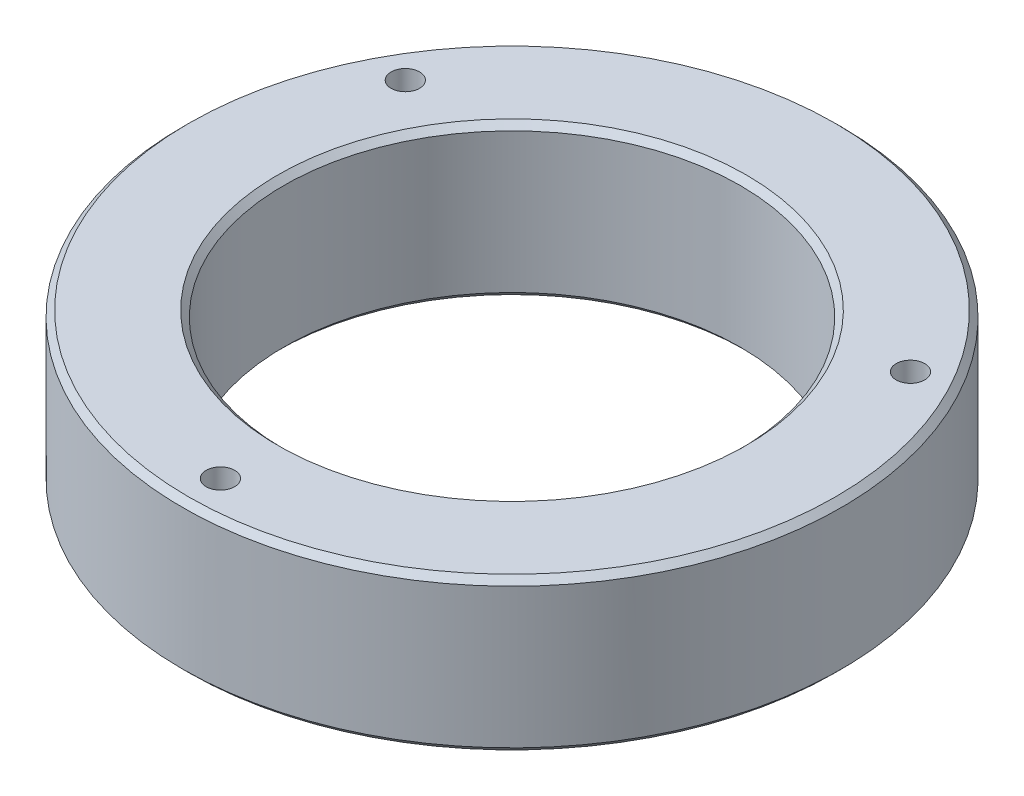
SolidWorks part; units mm, degrees
ref_plane "Front Plane" through (0, 0, 0) normal (1, 0, 0) x (0, 1, 0)
ref_plane "Top Plane" through (0, 0, 0) normal (0, 0, 1) x (0, 1, 0)
ref_plane "Right Plane" through (0, 0, 0) normal (0, 1, 0) x (-1, 0, 0)
sketch "Sketch1" plane through (0, 0, 0) normal (0, 0, 1) x (0, 1, 0)
  line L0 (-19.05, 82.5246) -> (19.05, 82.5246)
  line L1 (19.05, 82.5246) -> (19.05, 57.15)
  line L2 (19.05, 57.15) -> (-19.05, 57.15)
  line L3 (-19.05, 57.15) -> (-19.05, 82.5246)
  line L4 (-44.45, 0) -> (44.45, 0) construction
  point P6 (0, 0)
  dimension "D1" = 38.1
  dimension "D2" = 25.3746
  dimension "D3" = 82.5246
  dimension "D4" = 19.05
revolve "Revolve1" add sketch "Sketch1" angle 360 about L4
hole_wizard "CBORE for 1/4 Socket Head Cap Screw1" positions "Sketch3" profile "Sketch2" counterbore size "1/4" standard "ANSI Inch"
sketch "Sketch3" plane through (0, -19.05, 0) normal (0, -1, 0) x (-1, 0, 0)
  circle A0 centre (0, 0.0068) radius 73.0318 construction
  circle A1 centre (0, 0) radius 57.15 construction
  point P0 (0, -73.025)
  point P1 (-63.246, 36.5252)
  point P3 (63.246, 36.5252)
  dimension "D1" = 146.0637
  dimension "D2" = 63.246
  dimension "D3" = 63.246
  dimension "D4" = 0.0068
  dimension "D5" = 36.5252
  dimension "D6" = 73.025
sketch "Sketch2" plane through (0, -19.05, 73.025) normal (1, 0, 0) x (0, 0, -1)
  line L0 (0, 0) -> (0, 40.2443)
  line L1 (0, 40.2443) -> (3.5687, 38.1)
  line L2 (3.5687, 38.1) -> (3.5687, 9.652)
  line L3 (3.5687, 9.652) -> (5.5626, 9.652)
  line L4 (5.5626, 9.652) -> (5.5626, 0)
  line L5 (5.5626, 0) -> (0, 0)
  line L10 (0, 40.2443) -> (-3.5687, 38.1) construction
  line L11 (0, -6.35) -> (0, 107.95) construction
  dimension "Hole Dia." = 7.1374
  dimension "Hole Depth" = 38.1
  dimension "C'Bore Dia." = 11.1252
  dimension "C'Bore Depth" = 9.652
  dimension "Drill Angle" = 118
hole_wizard "3/8-16 Tapped Hole2" positions "Sketch7" profile "Sketch6" tap size "3/8-16" standard "ANSI Inch"
sketch "Sketch7" plane through (0, -19.05, 0) normal (0, -1, 0) x (-1, 0, 0)
  circle A0 centre (0, -73.025) radius 5.5626 construction
  point P0 (-69.85, 0)
  point P1 (69.85, 0)
  dimension "D1" = 69.85
  dimension "D2" = 69.85
  dimension "D3" = 73.025
  dimension "D4" = 73.025
sketch "Sketch6" plane through (69.85, -19.05, 0) normal (1, 0, 0) x (0, 0, -1)
  line L0 (0, 0) -> (0, 27.7847)
  line L1 (0, 27.7847) -> (3.9687, 25.4)
  line L2 (3.9687, 25.4) -> (3.9687, 0)
  line L5 (3.9687, 0) -> (0, 0)
  line L10 (0, 27.7847) -> (-3.9687, 25.4) construction
  line L11 (0, -6.35) -> (0, 107.95) construction
  dimension "Tap Drill Dia." = 7.9375
  dimension "Tap Drill Depth" = 25.4
  dimension "Drill Angle" = 118
cosmetic thread "Hole Thread3" parameters "D1"=19.05, "D2"=9.525
cosmetic thread "Hole Thread4" parameters "D1"=19.05, "D2"=9.525
chamfer "Chamfer1" distance 1.524 angle 45 4 edges at (0, 19.05, -57.15) (0, -19.05, -57.15) (0, 19.05, -82.5246) (0, -19.05, -82.5246)
